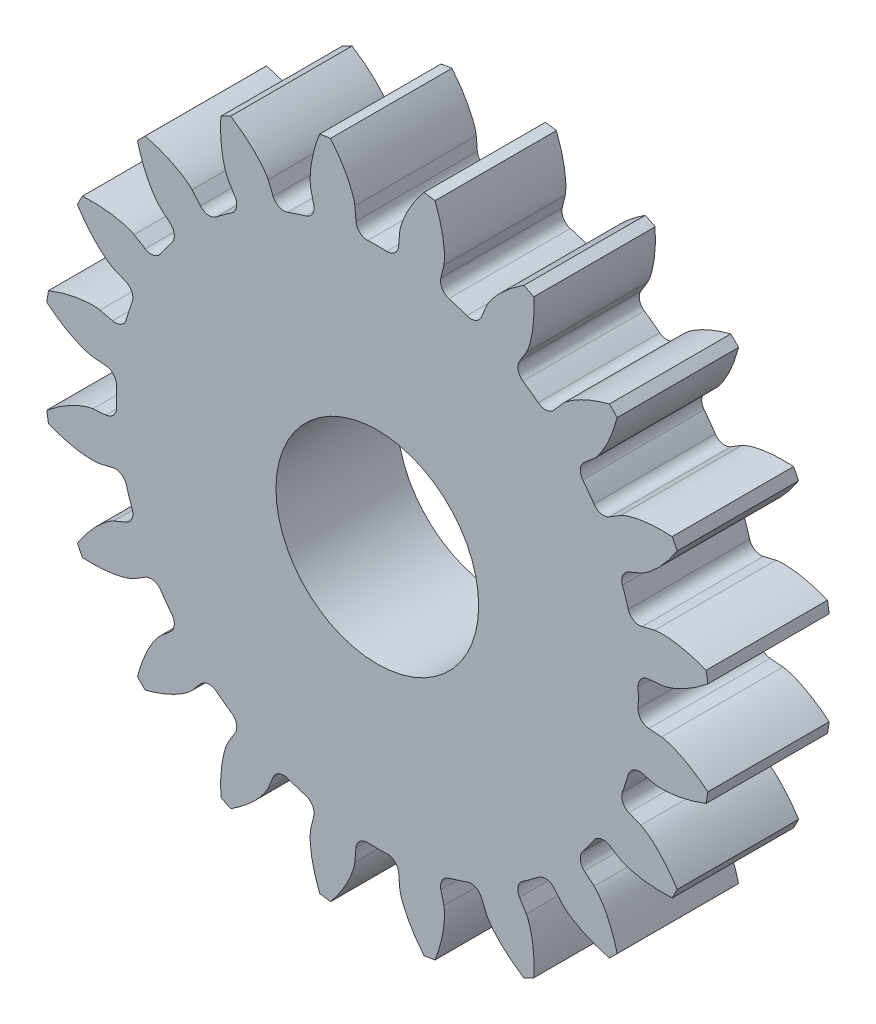
SolidWorks part; units mm, degrees
ref_plane "Front Plane" through (0, 0, 0) normal (0, 0, 1) x (1, 0, 0)
ref_plane "Top Plane" through (0, 0, 0) normal (0, 1, 0) x (1, 0, 0)
ref_plane "Right Plane" through (0, 0, 0) normal (1, 0, 0) x (0, 0, -1)
ref_axis "Gear Axis" through (0, 0, -0.2501) along (0, 0, 1)
sketch "Blank Sketch" plane through (0, 0, 0) normal (0, 0, 1) x (1, 0, 0)
  circle A0 centre (0, 0) radius 13.75
  dimension "OD" = 27.5
extrude "Blank" add sketch "Blank Sketch" along normal blind 5
sketch "Tooth Space Sketch" plane through (0, 0, 0) normal (0, 0, 1) x (1, 0, 0)
  line L0 (11.7099, 0.9227) -> (11.1803, 0.881)
  line L1 (11.7099, -0.9227) -> (11.1803, -0.881)
  line L2 (14.6961, 3.0042) -> (14.6961, -3.0042)
  arc A0 (11.1803, 0.881) -> (10.7429, 0.3902) centre (11.2176, 0.4075) ccw
  arc A1 (10.7429, -0.3902) -> (11.1803, -0.881) centre (11.2176, -0.4075) ccw
  arc A2 (10.7429, -0.3902) -> (10.7429, 0.3902) centre (0, 0) ccw
  spline S0 degree 4 poles (11.7099, 0.9227) (11.7153, 0.9232) (11.7306, 0.925) (11.7593, 0.9294) (11.806, 0.9382) (11.8651, 0.9517) (11.9409, 0.9719) (12.0295, 0.999) (12.1261, 1.0323) (12.2301, 1.0723) (12.3329, 1.1155) (12.4344, 1.1617) (12.5347, 1.2105) (12.6549, 1.2727) (12.7975, 1.3519) (12.9615, 1.4507) (13.1443, 1.5703) (13.3269, 1.7) (13.5034, 1.834) (13.678, 1.9766) (13.8441, 2.1196) (14.0125, 2.2754) (14.1658, 2.4228) (14.3326, 2.5956) (14.4659, 2.7374) (14.6362, 2.9324) (14.7351, 3.0499) (14.8489, 3.1902) (14.8984, 3.2539) (14.9289, 3.293) knots 0 0 0 0 0 0.005377 0.015084 0.028532 0.04661 0.064855 0.092111 0.119476 0.146842 0.174209 0.201575 0.228941 0.256307 0.307035 0.361767 0.4165 0.471232 0.525964 0.580697 0.635429 0.690161 0.744894 0.799626 0.854358 0.909091 0.954545 1 1 1 1 1 construction
  spline S1 degree 4 poles (11.7099, 0.9227) (11.7153, 0.9232) (11.7306, 0.925) (11.7593, 0.9294) (11.806, 0.9382) (11.8651, 0.9517) (11.9409, 0.9719) (12.0295, 0.999) (12.1261, 1.0323) (12.2301, 1.0723) (12.3329, 1.1155) (12.4344, 1.1617) (12.5347, 1.2105) (12.6549, 1.2727) (12.7975, 1.3519) (12.9615, 1.4507) (13.1443, 1.5703) (13.3269, 1.7) (13.5034, 1.834) (13.678, 1.9766) (13.8441, 2.1196) (14.0125, 2.2754) (14.1658, 2.4228) (14.3326, 2.5956) (14.4659, 2.7374) (14.5992, 2.8901) (14.6635, 2.9654) (14.6961, 3.0042) knots 0 0 0 0 0 0.005377 0.015084 0.028532 0.04661 0.064855 0.092111 0.119476 0.146842 0.174209 0.201575 0.228941 0.256307 0.307035 0.361767 0.4165 0.471232 0.525964 0.580697 0.635429 0.690161 0.744894 0.799626 0.854358 0.909091 0.909091 0.909091 0.909091 0.909091
  spline S2 degree 4 poles (11.7099, -0.9227) (11.7153, -0.9232) (11.7306, -0.925) (11.7593, -0.9294) (11.806, -0.9382) (11.8651, -0.9517) (11.9409, -0.9719) (12.0295, -0.999) (12.1261, -1.0323) (12.2301, -1.0723) (12.3329, -1.1155) (12.4344, -1.1617) (12.5347, -1.2105) (12.6549, -1.2727) (12.7975, -1.3519) (12.9615, -1.4507) (13.1443, -1.5703) (13.3269, -1.7) (13.5034, -1.834) (13.678, -1.9766) (13.8441, -2.1196) (14.0125, -2.2754) (14.1658, -2.4228) (14.3326, -2.5956) (14.4659, -2.7374) (14.6362, -2.9324) (14.7351, -3.0499) (14.8489, -3.1902) (14.8984, -3.2539) (14.9289, -3.293) knots 0 0 0 0 0 0.005377 0.015084 0.028532 0.04661 0.064855 0.092111 0.119476 0.146842 0.174209 0.201575 0.228941 0.256307 0.307035 0.361767 0.4165 0.471232 0.525964 0.580697 0.635429 0.690161 0.744894 0.799626 0.854358 0.909091 0.954545 1 1 1 1 1 construction
  spline S3 degree 4 poles (11.7099, -0.9227) (11.7153, -0.9232) (11.7306, -0.925) (11.7593, -0.9294) (11.806, -0.9382) (11.8651, -0.9517) (11.9409, -0.9719) (12.0295, -0.999) (12.1261, -1.0323) (12.2301, -1.0723) (12.3329, -1.1155) (12.4344, -1.1617) (12.5347, -1.2105) (12.6549, -1.2727) (12.7975, -1.3519) (12.9615, -1.4507) (13.1443, -1.5703) (13.3269, -1.7) (13.5034, -1.834) (13.678, -1.9766) (13.8441, -2.1196) (14.0125, -2.2754) (14.1658, -2.4228) (14.3326, -2.5956) (14.4659, -2.7374) (14.5992, -2.8901) (14.6635, -2.9654) (14.6961, -3.0042) knots 0 0 0 0 0 0.005377 0.015084 0.028532 0.04661 0.064855 0.092111 0.119476 0.146842 0.174209 0.201575 0.228941 0.256307 0.307035 0.361767 0.4165 0.471232 0.525964 0.580697 0.635429 0.690161 0.744894 0.799626 0.854358 0.909091 0.909091 0.909091 0.909091 0.909091
  dimension "Root" = 10.75
  dimension "Fillet" = 0.475
extrude "Tooth Space" cut sketch "Tooth Space Sketch" against normal through all both and the other way through all both
pattern_circular "Teeth" count 20 over 360 about axis through (0, 0, -0.2501) along (0, 0, 1) of "Tooth Space"
sketch "Bore Sketch" plane through (0, 0, 0) normal (0, 0, 1) x (1, 0, 0)
  circle A0 centre (0, 0) radius 4.175
  dimension "Bore" = 8.35
extrude "Bore" cut sketch "Bore Sketch" against normal through all both and the other way through all both
equation "\"No. of Teeth\"= 20"
equation "\"Module\"= 1.25"
equation "\"Bore Diameter\" = 8.35"
equation "\"Pressure Angle\"= 20"
equation "\"Outer Diameter\"= ( \"No. of Teeth\" + 2 ) * \"Module\""
equation "\"Pitch Diameter\"= \"No. of Teeth\" * \"Module\""
equation "\"Backlash\"= 0.3 * \"Module\""
equation "\"Arc Length\"= ( ( \"Module\" * pi ) / 2 + \"Backlash\" )"
equation "\"Fillet Radius\"= 0.38 * \"Module\""
equation "\"Tooth Depth\"= IIF ( \"Module\" <= 1.25 , \"Module\" * 2.4 , \"Module\" * 2.25 )"
equation "\"Face Width\"= 5"
equation "\"Root Diameter\"= \"Outer Diameter\" - 2 * \"Tooth Depth\""
equation "\"Base Diameter\"= \"Pitch Diameter\" * cos ( \"Pressure Angle\" )"
equation "\"Base Radius\"= \"Base Diameter\" / 2"
equation "\"Tooth Thickness\"= \"Module\" * pi - \"Arc Length\""
equation "\"Half Space Angle\"= ( \"Arc Length\" / \"Pitch Diameter\" ) * 180 / pi"
equation "\"Involute Fn\"= tan ( \"Pressure Angle\" ) - \"Pressure Angle\" * pi / 180"
equation "\"Flank Offset\"= \"Arc Length\" / \"Pitch Diameter\" - \"Involute Fn\""
equation "\"Tip Cap Diameter\"= \"Outer Diameter\" + 2 * \"Module\""
equation "\"Flank Start Diameter\"= IIF ( \"Base Diameter\" >= ( \"Root Diameter\" + 3 * \"Fillet Radius\" ) , \"Base Diameter\" , \"Root Diameter\" + 3 * \"Fillet Radius\" )"
equation "\"Involute t1\"= ( abs ( ( \"Flank Start Diameter\" / \"Base Diameter\" ) ^ 2 - 1 ) ) ^ 0.5"
equation "\"Involute t2\"= ( abs ( ( \"Tip Cap Diameter\" / \"Base Diameter\" ) ^ 2 - 1 ) ) ^ 0.5"
equation "\"Flank Arc Radius\"= ( \"Pitch Diameter\" / 2 ) * sin ( \"Pressure Angle\" )"
equation "\"Flank Centre Angle\"= \"Half Space Angle\" + \"Pressure Angle\""
equation "\"OD@Blank Sketch\"= \"Outer Diameter\""
equation "\"Width@Blank\"= \"Face Width\""
equation "\"Root@Tooth Space Sketch\"= \"Root Diameter\" / 2"
equation "\"Fillet@Tooth Space Sketch\"= \"Fillet Radius\""
equation "\"Count@Teeth\"= \"No. of Teeth\""
equation "\"Bore@Bore Sketch\"= \"Bore Diameter\""
